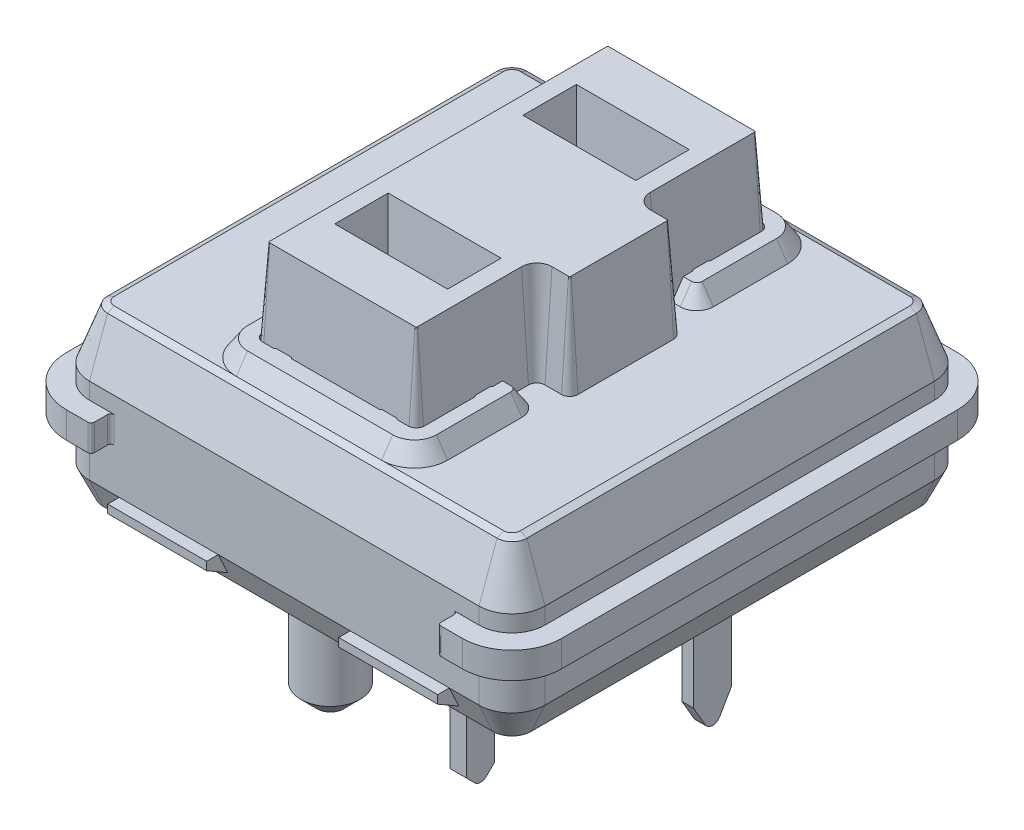
SolidWorks part; units mm, degrees
ref_plane "Front Plane" through (0, 0, 0) normal (0, 0, 1) x (1, 0, 0)
ref_plane "Top Plane" through (0, 0, 0) normal (0, 1, 0) x (1, 0, 0)
ref_plane "Right Plane" through (0, 0, 0) normal (1, 0, 0) x (0, 0, -1)
sketch "Sketch1" plane through (0, 0, 0) normal (0, 1, 0) x (1, 0, 0)
  line L0 (-12.6999, -17.2743) -> (27.7413, -17.2743) construction
  line L1 (-6, 7.5) -> (6, 7.5)
  line L2 (-7.5, 6) -> (-7.5, -6)
  line L3 (-6, -7.5) -> (6, -7.5)
  line L4 (7.5, 6) -> (7.5, -6)
  line L5 (-7.5, 7.5) -> (7.5, -7.5) construction
  line L6 (-7.5, -7.5) -> (7.5, 7.5) construction
  arc A0 (-7.5, -6) -> (-6, -7.5) centre (-6, -6) ccw
  arc A1 (6, -7.5) -> (7.5, -6) centre (6, -6) ccw
  arc A2 (6, 7.5) -> (7.5, 6) centre (6, 6) cw
  arc A3 (-6, 7.5) -> (-7.5, 6) centre (-6, 6) ccw
  point P0 (0, 0)
  dimension "D3" = 1.5
  dimension "D1" = 15
  dimension "D2" = 15
sketch "Sketch5" plane through (0, 0, 0) normal (0, 1, 0) x (1, 0, 0)
  line L1 (6, -7.5) -> (-6, -7.5)
  line L2 (7.5, -6) -> (7.5, 6)
  line L3 (6, 7.5) -> (-6, 7.5)
  line L4 (-7.5, -6) -> (-7.5, 6)
  line L5 (7.5, -7.5) -> (-7.5, 7.5) construction
  line L6 (7.5, 7.5) -> (-7.5, -7.5) construction
  arc A0 (-6, -7.5) -> (-7.5, -6) centre (-6, -6) cw
  arc A1 (6, -7.5) -> (7.5, -6) centre (6, -6) ccw
  arc A2 (7.5, 6) -> (6, 7.5) centre (6, 6) ccw
  arc A3 (-6, 7.5) -> (-7.5, 6) centre (-6, 6) ccw
  point P0 (0, 0)
  dimension "D1" = 1.5
extrude "Boss-Extrude4" add sketch "Sketch5" along normal mid plane 0.8
sketch "Sketch6" plane through (0, 0.4, 0) normal (0, 1, 0) x (1, 0, 0)
  line L0 (-7.5, 7.5) -> (7.5, -7.5) construction
  line L1 (5.9, -6.9) -> (-5.9, -6.9)
  line L2 (6.9, -5.9) -> (6.9, 5.9)
  line L3 (5.9, 6.9) -> (-5.9, 6.9)
  line L4 (-6.9, -5.9) -> (-6.9, 5.9)
  line L5 (6.9, -6.9) -> (-6.9, 6.9) construction
  line L6 (6.9, 6.9) -> (-6.9, -6.9) construction
  arc A0 (-5.9, -6.9) -> (-6.9, -5.9) centre (-5.9, -5.9) cw
  arc A1 (5.9, -6.9) -> (6.9, -5.9) centre (5.9, -5.9) ccw
  arc A2 (6.9, 5.9) -> (5.9, 6.9) centre (5.9, 5.9) ccw
  arc A3 (-5.9, 6.9) -> (-6.9, 5.9) centre (-5.9, 5.9) ccw
  point P0 (0, 0)
  dimension "D2" = 1
  dimension "D1" = 13.8
extrude "Boss-Extrude5" add sketch "Sketch6" along normal blind 0.5
sketch "Sketch7" plane through (0, 0.9, 0) normal (0, 1, 0) x (1, 0, 0)
  line L4 (-5.9, -6.9) -> (5.9, -6.9)
  line L5 (6.9, -5.9) -> (6.9, 5.9)
  line L6 (5.9, 6.9) -> (-5.9, 6.9)
  line L7 (-6.9, 5.9) -> (-6.9, -5.9)
  line L8 (-5.9, -6.9) -> (5.9, -6.9)
  line L9 (6.9, -5.9) -> (6.9, 5.9)
  line L10 (5.9, 6.9) -> (-5.9, 6.9)
  line L11 (-6.9, 5.9) -> (-6.9, -5.9)
  arc A4 (-6.9, -5.9) -> (-5.9, -6.9) centre (-5.9, -5.9) ccw
  arc A5 (5.9, -6.9) -> (6.9, -5.9) centre (5.9, -5.9) ccw
  arc A6 (6.9, 5.9) -> (5.9, 6.9) centre (5.9, 5.9) ccw
  arc A7 (-5.9, 6.9) -> (-6.9, 5.9) centre (-5.9, 5.9) ccw
  arc A8 (-6.9, -5.9) -> (-5.9, -6.9) centre (-5.9, -5.9) ccw
  arc A9 (5.9, -6.9) -> (6.9, -5.9) centre (5.9, -5.9) ccw
  arc A10 (6.9, 5.9) -> (5.9, 6.9) centre (5.9, 5.9) ccw
  arc A11 (-5.9, 6.9) -> (-6.9, 5.9) centre (-5.9, 5.9) ccw
  arc M9 (-6.9, -5.9) -> (-5.9, -6.9) centre (-5.9, -5.9) ccw
  line M10 (-5.9, -6.9) -> (5.9, -6.9)
  arc M11 (5.9, -6.9) -> (6.9, -5.9) centre (5.9, -5.9) ccw
  line M12 (6.9, -5.9) -> (6.9, 5.9)
  arc M13 (6.9, 5.9) -> (5.9, 6.9) centre (5.9, 5.9) ccw
  line M14 (5.9, 6.9) -> (-5.9, 6.9)
  arc M15 (-5.9, 6.9) -> (-6.9, 5.9) centre (-5.9, 5.9) ccw
  line M16 (-6.9, 5.9) -> (-6.9, -5.9)
  dimension "D1" = 0
extrude "Boss-Extrude6" add sketch "Sketch7" along normal offset from surface 2.5 draft 20 contours M16 M9 M10 M11 M12 M13 M14 M15
chamfer "Chamfer1" distance 0.1 angle 45 8 edges at (0, 2.5, -6.3176) (6.1953, 2.5, -6.1953) (6.3176, 2.5, 0) (6.1953, 2.5, 6.1953) (0, 2.5, 6.3176) (-6.1953, 2.5, 6.1953) (-6.3176, 2.5, 0) (-6.1953, 2.5, -6.1953)
sketch "Sketch8" plane through (0, 2.5, 0) normal (0, 1, 0) x (1, 0, 0)
  line L0 (5.9, 6.1503) -> (-5.9, 6.1503) construction
  line L1 (2.2, -6.1503) -> (-2.2, -6.1503)
  line L2 (3.2, -5.1503) -> (3.2, -2.9003)
  line L3 (2.2, 6.1503) -> (-2.2, 6.1503)
  line L4 (-3.2, -5.1503) -> (-3.2, 5.1503)
  line L5 (3.2, -6.1503) -> (-3.2, 6.1503) construction
  line L6 (3.2, 6.1503) -> (-3.2, -6.1503) construction
  line L7 (2.7, 2.4003) -> (2.3, 2.4003)
  line L8 (2.3, 2.4003) -> (2.3, -2.4003)
  line L9 (2.3, -2.4003) -> (2.7, -2.4003)
  line L10 (3.2, 2.9003) -> (3.2, 5.1503)
  arc A0 (-2.2, -6.1503) -> (-3.2, -5.1503) centre (-2.2, -5.1503) cw
  arc A1 (2.2, -6.1503) -> (3.2, -5.1503) centre (2.2, -5.1503) ccw
  arc A2 (3.2, 5.1503) -> (2.2, 6.1503) centre (2.2, 5.1503) ccw
  arc A3 (-2.2, 6.1503) -> (-3.2, 5.1503) centre (-2.2, 5.1503) ccw
  arc A4 (2.7, -2.4003) -> (3.2, -2.9003) centre (2.7, -2.9003) cw
  arc A5 (2.7, 2.4003) -> (3.2, 2.9003) centre (2.7, 2.9003) ccw
  point P0 (0, 0)
  point P28 (3.2, 2.4003)
  dimension "D2" = 1
  dimension "D5" = 0.5
  dimension "D1" = 6.4
  dimension "D3" = 3.75
  dimension "D4" = 0.9
extrude "Boss-Extrude7" add sketch "Sketch8" along normal blind 0.5 draft 34
sketch "Sketch9" plane through (0, 2.5, 0) normal (0, 1, 0) x (1, 0, 0)
  line L1 (-2.2, -5.35) -> (2.2, -5.35)
  line L2 (-2.45, -5.1) -> (-2.45, 5.1)
  line L3 (-2.2, 5.35) -> (2.2, 5.35)
  line L4 (2.45, -5.1) -> (2.45, 5.1)
  line L5 (-2.45, -5.35) -> (2.45, 5.35) construction
  line L6 (-2.45, 5.35) -> (2.45, -5.35) construction
  arc A0 (-2.2, -5.35) -> (-2.45, -5.1) centre (-2.2, -5.1) cw
  arc A1 (2.2, -5.35) -> (2.45, -5.1) centre (2.2, -5.1) ccw
  arc A2 (2.2, 5.35) -> (2.45, 5.1) centre (2.2, 5.1) cw
  arc A3 (-2.45, 5.1) -> (-2.2, 5.35) centre (-2.2, 5.1) cw
  point P0 (0, 0)
  dimension "D2" = 0.25
  dimension "D1" = 10.7
  dimension "D3" = 4.9
extrude "Cut-Extrude1" cut sketch "Sketch9" along normal through all
sketch "Sketch11" plane through (0, 2.5, 0) normal (0, 1, 0) x (1, 0, 0)
  line L0 (2.2, 5.35) -> (-2.2, 5.35) construction
  line L1 (2.45, 2.7376) -> (2.45, 5.1) construction
  line L2 (-2.45, 5.1) -> (-2.45, -5.1) construction
  line L3 (-2.2, -5.35) -> (2.2, -5.35) construction
  line L4 (2.45, -5.1) -> (2.45, -2.7376) construction
  line L5 (-1.8598, 5.35) -> (-1.3402, 5.35)
  line L6 (1.3402, 5.35) -> (1.8598, 5.35)
  line L7 (2.45, 3.5598) -> (2.45, 3.0402)
  line L8 (2.45, -3.0402) -> (2.45, -3.5598)
  line L9 (1.8598, -5.35) -> (1.3402, -5.35)
  line L10 (-1.3402, -5.35) -> (-1.8598, -5.35)
  line L11 (-2.45, -3.5598) -> (-2.45, -3.0402)
  line L12 (-2.45, 3.0402) -> (-2.45, 3.5598)
  line L13 (0, 0) -> (-1.4423, 0) construction
  line L14 (0, 0) -> (0, 1.7321) construction
  arc A0 (-1.8598, 5.35) -> (-1.3402, 5.35) centre (-1.6, 5.5) ccw
  arc A1 (1.3402, 5.35) -> (1.8598, 5.35) centre (1.6, 5.5) ccw
  arc A2 (2.45, 3.5598) -> (2.45, 3.0402) centre (2.6, 3.3) ccw
  arc A3 (-2.45, 3.5598) -> (-2.45, 3.0402) centre (-2.6, 3.3) cw
  arc A4 (-2.45, -3.0402) -> (-2.45, -3.5598) centre (-2.6, -3.3) cw
  arc A5 (-1.8598, -5.35) -> (-1.3402, -5.35) centre (-1.6, -5.5) cw
  arc A6 (1.3402, -5.35) -> (1.8598, -5.35) centre (1.6, -5.5) cw
  arc A7 (2.45, -3.0402) -> (2.45, -3.5598) centre (2.6, -3.3) ccw
  dimension "D1" = 0.3
  dimension "D2" = 0.15
  dimension "D3" = 1.6
  dimension "D4" = 3.3
extrude "Boss-Extrude8" add sketch "Sketch11" along normal up to surface (0.5 mm away) up to face at (0.7315, 3, 0)
sketch "Sketch12" plane through (0, 2.5, 0) normal (0, 1, 0) x (1, 0, 0)
  line L0 (2.7, 1.7) -> (3.2, 1.7)
  line L1 (2.2, 5.35) -> (-2.2, 5.35)
  line L2 (2.45, 5.1) -> (2.45, 1.95)
  line L3 (2.2, -5.35) -> (-2.2, -5.35)
  line L4 (-2.45, 5.1) -> (-2.45, -5.1)
  line L5 (2.45, 5.35) -> (-2.45, -5.35) construction
  line L6 (2.45, -5.35) -> (-2.45, 5.35) construction
  line L7 (3.45, 1.45) -> (3.45, -1.45)
  line L8 (3.2, -1.7) -> (2.7, -1.7)
  line L9 (2.45, -1.95) -> (2.45, -5.1)
  line L10 (-1.5, -2.25) -> (1.5, -3.45) construction
  line L11 (-1.5, -2.25) -> (1.5, -2.25)
  line L12 (-1.5, -2.25) -> (-1.5, -3.45)
  line L13 (-1.5, -3.45) -> (1.5, -3.45)
  line L14 (1.5, -2.25) -> (1.5, -3.45)
  line L15 (0, 0) -> (-1.3542, 0) construction
  line L16 (1.5, 2.25) -> (1.5, 3.45)
  line L17 (-1.5, 3.45) -> (1.5, 3.45)
  line L18 (-1.5, 2.25) -> (-1.5, 3.45)
  line L19 (-1.5, 2.25) -> (1.5, 2.25)
  arc A0 (-2.2, -5.35) -> (-2.45, -5.1) centre (-2.2, -5.1) cw
  arc A1 (2.45, -5.1) -> (2.2, -5.35) centre (2.2, -5.1) cw
  arc A2 (2.7, -1.7) -> (2.45, -1.95) centre (2.7, -1.95) ccw
  arc A3 (-2.2, 5.35) -> (-2.45, 5.1) centre (-2.2, 5.1) ccw
  arc A4 (2.2, 5.35) -> (2.45, 5.1) centre (2.2, 5.1) cw
  arc A5 (2.7, 1.7) -> (2.45, 1.95) centre (2.7, 1.95) cw
  arc A6 (3.2, 1.7) -> (3.45, 1.45) centre (3.2, 1.45) cw
  arc A7 (3.45, -1.45) -> (3.2, -1.7) centre (3.2, -1.45) cw
  point P0 (0, 0)
  point P18 (2.45, -1.7)
  point P29 (3.45, 1.7)
  point P32 (3.45, -1.7)
  point P37 (0, -2.85)
  dimension "D5" = 0.25
  dimension "D1" = 4.9
  dimension "D2" = 10.7
  dimension "D3" = 1
  dimension "D4" = 3.4
  dimension "D6" = 1.2
  dimension "D7" = 3
  dimension "D8" = 5.7
extrude "Boss-Extrude9" add sketch "Sketch12" along normal blind 3 draft 4
sketch "Sketch15" plane through (0, 0, 0) normal (0, 1, 0) x (1, 0, 0)
  line L0 (22.7981, 9.2794) -> (-33.7496, 9.2794) construction
sketch "Sketch16" plane through (0, -0.4, 0) normal (0, -1, 0) x (1, 0, 0)
  line L1 (5.9, -6.9) -> (-5.9, -6.9)
  line L2 (6.9, -5.9) -> (6.9, 5.9)
  line L3 (5.9, 6.9) -> (-5.9, 6.9)
  line L4 (-6.9, -5.9) -> (-6.9, 5.9)
  line L5 (6.9, -6.9) -> (-6.9, 6.9) construction
  line L6 (6.9, 6.9) -> (-6.9, -6.9) construction
  arc A0 (-5.9, -6.9) -> (-6.9, -5.9) centre (-5.9, -5.9) cw
  arc A1 (5.9, -6.9) -> (6.9, -5.9) centre (5.9, -5.9) ccw
  arc A2 (6.9, 5.9) -> (5.9, 6.9) centre (5.9, 5.9) ccw
  arc A3 (-6.9, 5.9) -> (-5.9, 6.9) centre (-5.9, 5.9) cw
  point P0 (0, 0)
  dimension "D2" = 1
  dimension "D1" = 13.8
extrude "Boss-Extrude10" add sketch "Sketch16" along normal blind 1.3
sketch "Sketch17" plane through (0, -1.7, 0) normal (0, -1, 0) x (1, 0, 0)
  line L4 (-5.9, -6.9) -> (5.9, -6.9)
  line L5 (6.9, -5.9) -> (6.9, 5.9)
  line L6 (5.9, 6.9) -> (-5.9, 6.9)
  line L7 (-6.9, 5.9) -> (-6.9, -5.9)
  line L8 (-5.9, -6.9) -> (5.9, -6.9)
  line L9 (6.9, -5.9) -> (6.9, 5.9)
  line L10 (5.9, 6.9) -> (-5.9, 6.9)
  line L11 (-6.9, 5.9) -> (-6.9, -5.9)
  arc A4 (-6.9, -5.9) -> (-5.9, -6.9) centre (-5.9, -5.9) ccw
  arc A5 (5.9, -6.9) -> (6.9, -5.9) centre (5.9, -5.9) ccw
  arc A6 (6.9, 5.9) -> (5.9, 6.9) centre (5.9, 5.9) ccw
  arc A7 (-5.9, 6.9) -> (-6.9, 5.9) centre (-5.9, 5.9) ccw
  arc A8 (-6.9, -5.9) -> (-5.9, -6.9) centre (-5.9, -5.9) ccw
  arc A9 (5.9, -6.9) -> (6.9, -5.9) centre (5.9, -5.9) ccw
  arc A10 (6.9, 5.9) -> (5.9, 6.9) centre (5.9, 5.9) ccw
  arc A11 (-5.9, 6.9) -> (-6.9, 5.9) centre (-5.9, 5.9) ccw
  dimension "D1" = 0
extrude "Boss-Extrude11" add sketch "Sketch17" along normal blind 0.9 draft 25
sketch "Sketch18" plane through (0, -2.6, 0) normal (0, -1, 0) x (1, 0, 0)
  line L1 (-6.275, 2.5) -> (-3.125, 2.5)
  line L2 (-6.275, 2.5) -> (-6.275, -2.5)
  line L3 (-6.275, -2.5) -> (-3.125, -2.5)
  line L4 (-3.125, 2.5) -> (-3.125, -2.5)
  line L5 (-6.275, 2.5) -> (-3.125, -2.5) construction
  line L6 (-6.275, -2.5) -> (-3.125, 2.5) construction
  point P0 (-4.7, 0)
  dimension "D1" = 3.15
  dimension "D2" = 5
  dimension "D3" = 4.7
extrude "Cut-Extrude4" cut sketch "Sketch18" against normal blind 4
sketch "Sketch19" plane through (0, -2.6, 0) normal (0, -1, 0) x (1, 0, 0)
  line L0 (0, 0) -> (2.7131, 0) construction
  circle A0 centre (0, 0) radius 1.6
  circle A1 centre (0, 5.5) radius 0.9
  circle A3 centre (0, -5.5) radius 0.9
  dimension "D1" = 3.2
  dimension "D3" = 1.8
  dimension "D2" = 11
extrude "Boss-Extrude12" add sketch "Sketch19" along normal blind 2.65
chamfer "Chamfer2" distance 0.5 angle 45 3 edges at (0, -5.25, -4.6) (0, -5.25, -1.6) (0, -5.25, 4.6)
sketch "Sketch20" plane through (0, -2.6, 0) normal (0, -1, 0) x (1, 0, 0)
  line L1 (5.725, 0.575) -> (6.075, 0.575)
  line L2 (5.725, 0.575) -> (5.725, -0.575)
  line L3 (5.725, -0.575) -> (6.075, -0.575)
  line L4 (6.075, 0.575) -> (6.075, -0.575)
  line L5 (5.725, 0.575) -> (6.075, -0.575) construction
  line L6 (5.725, -0.575) -> (6.075, 0.575) construction
  line L8 (3.55, 5.425) -> (4.05, 5.425)
  line L9 (3.55, 5.425) -> (3.55, 4.575)
  line L10 (3.55, 4.575) -> (4.05, 4.575)
  line L11 (4.05, 5.425) -> (4.05, 4.575)
  line L12 (3.55, 5.425) -> (4.05, 4.575) construction
  line L13 (3.55, 4.575) -> (4.05, 5.425) construction
  point P0 (5.9, 0)
  point P5 (3.8, 5)
  dimension "D1" = 1.15
  dimension "D2" = 0.35
  dimension "D3" = 5.9
  dimension "D4" = 0.5
  dimension "D5" = 0.85
  dimension "D6" = 5
  dimension "D7" = 3.8
extrude "Boss-Extrude13" add sketch "Sketch20" along normal blind 3
sketch "Sketch21" plane through (6.075, 0, 0) normal (1, 0, 0) x (0, 0, -1)
  line L0 (0, -5.6) -> (0, -3.8431) construction
  line L1 (0.575, -5.6) -> (-0.575, -5.6) construction
  line L2 (-5, -5.6) -> (-5, -3.8431) construction
  line L3 (-4.575, -5.6) -> (-5.425, -5.6) construction
  line L4 (-0.575, -4.8541) -> (-0.2165, -5.475)
  line L5 (-0.575, -5.6) -> (-0.575, -2.6) construction
  line L6 (0.575, -4.8541) -> (0.2165, -5.475)
  line L7 (0.575, -5.6) -> (0.575, -2.6) construction
  line L8 (-5.425, -5.2786) -> (-5.1768, -5.5268)
  line L9 (-5.425, -5.6) -> (-5.425, -2.6) construction
  line L10 (-4.575, -5.2786) -> (-4.8232, -5.5268)
  line L11 (-4.575, -5.6) -> (-4.575, -2.6) construction
  line L12 (-0.575, -4.8541) -> (-0.575, -5.7)
  line L13 (-0.575, -5.7) -> (-4.575, -5.7)
  line L14 (-4.575, -5.7) -> (-4.575, -5.2786)
  line L16 (-5.425, -5.2786) -> (-5.425, -6.7)
  line L17 (-5.425, -6.7) -> (0.575, -6.7)
  line L18 (0.575, -6.7) -> (0.575, -4.8541)
  arc A0 (-0.2165, -5.475) -> (0.2165, -5.475) centre (0, -5.35) ccw
  arc A1 (-5.1768, -5.5268) -> (-4.8232, -5.5268) centre (-5, -5.35) ccw
  dimension "D1" = 0.5
  dimension "D2" = 30
  dimension "D3" = 45
  dimension "D4" = 0.1
  dimension "D5" = 1
extrude "Cut-Extrude5" cut sketch "Sketch21" against normal up to surface (2.525 mm away) up to face at (3.55, -4.1, 5)
sketch "Sketch22" plane through (0, 0, 0) normal (1, 0, 0) x (0, 0, -1)
  line L0 (-13.7977, 33.6254) -> (-14.1977, -19.6321) construction
  line L1 (-6.9, -1.7) -> (-7.25, -1.7)
  line L2 (-7.25, -1.7) -> (-7.25, -1.95)
  line L3 (-7.25, -1.95) -> (-6.6115, -2.3186)
  line L4 (-6.4803, -2.6) -> (-6.9, -1.7) construction
  line L5 (-6.6115, -2.3186) -> (-6.9, -1.7)
  line L6 (0, 0) -> (0, -3.4947) construction
  dimension "D1" = 14.5
  dimension "D2" = 30
  dimension "D3" = 0.25
extrude "Boss-Extrude14" add sketch "Sketch22" along normal blind 3 from offset 2
mirror "Mirror1" about plane through (0, 0, 0) normal (1, 0, 0) of "Boss-Extrude14"
mirror "Mirror2" about plane through (0, 0, 0) normal (0, 0, 1) of "Mirror1", "Boss-Extrude14"
sketch "Sketch23" plane through (0, -0.4, 0) normal (0, -1, 0) x (1, 0, 0)
  line L0 (-6, 7.5) -> (6, 7.5) construction
  line L1 (-5.25, 7.5) -> (5.25, 7.5)
  line L2 (-5.25, 7.5) -> (-5.25, 6.9)
  line L3 (-5.25, 6.9) -> (5.25, 6.9)
  line L4 (5.25, 7.5) -> (5.25, 6.9)
  line L5 (5.9, 6.9) -> (5, 6.9) construction
  line L6 (0, 0) -> (0, 6.9) construction
  line L7 (2, 6.9) -> (-2, 6.9) construction
  line L8 (0, 0) -> (-4.2254, 0) construction
  line L9 (5.25, -7.5) -> (5.25, -6.9)
  line L10 (-5.25, -6.9) -> (5.25, -6.9)
  line L11 (-5.25, -7.5) -> (-5.25, -6.9)
  line L12 (-5.25, -7.5) -> (5.25, -7.5)
  dimension "D1" = 10.5
extrude "Cut-Extrude6" cut sketch "Sketch23" against normal up to next
fillet "Fillet1" radius 0.1 8 edges at (-5.25, 0, 6.9) (5.25, 0, 6.9) (5.25, 0, -6.9) (-5.25, 0, -6.9) (-5.25, 0, -7.5) (5.25, 0, -7.5) (5.25, 0, 7.5) (-5.25, 0, 7.5)
